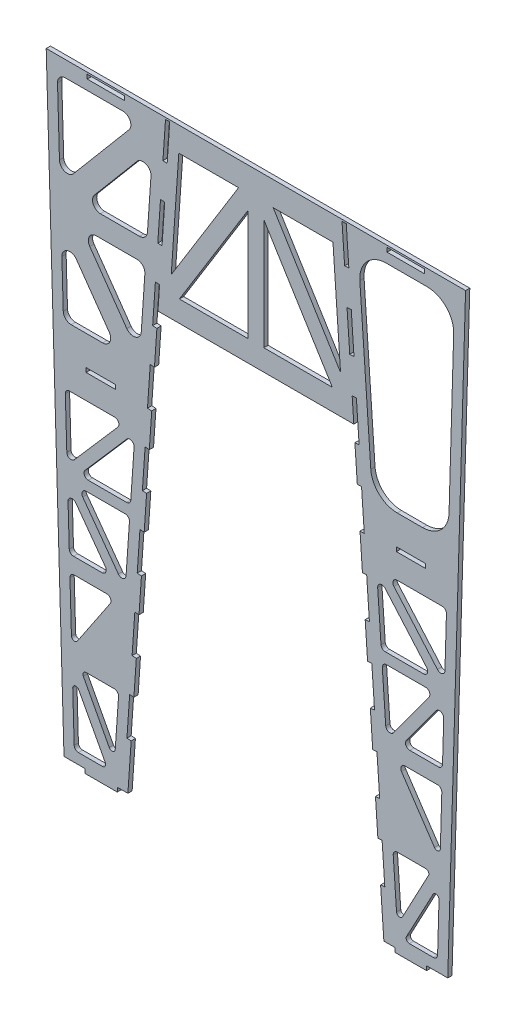
SolidWorks part; units mm, degrees
ref_plane "Front Plane" through (0, 0, 0) normal (0, 0, 1) x (1, 0, 0)
ref_plane "Top Plane" through (0, 0, 0) normal (0, 1, 0) x (1, 0, 0)
ref_plane "Right Plane" through (0, 0, 0) normal (1, 0, 0) x (0, 0, -1)
sketch "Sketch1" plane through (0, 0, 0) normal (0, 0, 1) x (1, 0, 0)
  line L0 (-288.2759, 0) -> (288.2759, 0) construction
  line L1 (-215.8925, 1465.1633) -> (215.8925, 1465.1633)
  line L2 (0, 0) -> (0, 1733.4513) construction
  line L3 (19.05, 1104.9) -> (205.6376, 1104.9)
  line L4 (202.8026, 1145.716) -> (41.4459, 1406.7433)
  line L5 (205.6376, 1104.9) -> (19.05, 1406.7433) construction
  line L6 (205.6376, 1104.9) -> (184.6725, 1406.7433)
  line L7 (183.2417, 1104.9) -> (15.2162, 1376.7154)
  line L8 (19.05, 1406.7433) -> (19.05, 1104.9)
  line L9 (184.6725, 1406.7433) -> (19.05, 1406.7433)
  line L10 (306.6278, 17.4764) -> (234.6272, 1054.1)
  line L11 (408.9218, 17.4764) -> (459.7218, 17.4764)
  line L12 (459.7218, 17.4764) -> (502.3797, 1465.1633)
  line L13 (459.4357, 7.4824) -> (519.9157, 2060.3987) construction
  line L14 (-408.9218, 17.4764) -> (-408.9218, 7.3164) construction
  line L15 (266.6925, 1465.1633) -> (368.5375, 1465.1633)
  line L16 (-237.2124, 1016.8799) -> (-230.6925, 1110.7494) construction
  line L18 (237.2124, 1016.8799) -> (230.6925, 1110.7494) construction
  line L19 (-408.9218, 7.3164) -> (-332.1008, 7.3164)
  line L20 (-502.3797, 1465.1633) -> (-215.8925, 1465.1633)
  line L21 (-408.9218, 17.4764) -> (-408.9218, 7.3164)
  line L22 (408.9218, 7.3164) -> (332.7218, 7.3164)
  line L31 (502.3797, 1465.1633) -> (368.5375, 1465.1633)
  line L33 (-332.1008, 17.4764) -> (-332.1008, 7.3164)
  line L35 (408.9218, 17.4764) -> (408.9218, 7.3164)
  line L43 (332.7218, 17.4764) -> (332.7218, 7.3164)
  line L49 (-408.9218, 17.4764) -> (-459.7218, 17.4764)
  line L52 (-332.1008, 17.4764) -> (-306.6278, 17.4764)
  line L53 (332.7218, 17.4764) -> (306.6278, 17.4764)
  line L55 (-459.7218, 17.4764) -> (-502.3797, 1465.1633)
  line L56 (-459.4357, 7.4824) -> (-519.9157, 2060.3987) construction
  line L81 (215.8925, 1465.1633) -> (266.6925, 1465.1633)
  line L90 (234.6272, 1054.1) -> (-234.6272, 1054.1)
  line L100 (-234.6272, 1054.1) -> (-306.6278, 17.4764)
  line L124 (-184.6725, 1406.7433) -> (-19.05, 1406.7433)
  line L125 (-19.05, 1406.7433) -> (-19.05, 1104.9)
  line L126 (-183.2417, 1104.9) -> (-15.2162, 1376.7154)
  line L127 (-205.6376, 1104.9) -> (-19.05, 1406.7433) construction
  line L128 (-202.8026, 1145.716) -> (-41.4459, 1406.7433)
  line L129 (-205.6376, 1104.9) -> (-184.6725, 1406.7433)
  line L130 (-19.05, 1104.9) -> (-205.6376, 1104.9)
  point P0 (0, 0)
  point P3 (0, 0)
  point P106 (0, 0)
  point P118 (0, 1054.1)
  dimension "D6" = 25.4
  dimension "D7" = 50.8
  dimension "D8" = 58.42
  dimension "D9" = 19.05
  dimension "D19" = 288.2759
  dimension "D22" = 19.05
  dimension "D23" = 19.05
  dimension "D24" = 1054.1
  dimension "D49" = 50.8
extrude "Boss-Extrude1" add sketch "Sketch1" along normal blind 10.16
fillet "Fillet1" [suppressed] radius 19.05
sketch "Sketch2" plane through (0, 0, 0) normal (0, 0, 1) x (1, 0, 0)
  line L18 (-222.6942, 1372.2749) -> (-212.5765, 1371.5721) construction
  line L56 (-216.5353, 1460.9479) -> (-222.6942, 1372.2749) construction
  line L57 (-212.5765, 1371.5721) -> (-206.3688, 1460.9479) construction
  line L58 (-206.3688, 1460.9479) -> (-216.5353, 1460.9479) construction
  line L59 (-222.6942, 1372.2749) -> (-212.5765, 1371.5721)
  line L61 (-216.5353, 1460.9479) -> (-222.6942, 1372.2749)
  line L63 (-212.5765, 1371.5721) -> (-206.3688, 1460.9479)
  line L176 (-206.3688, 1460.9479) -> (-216.5353, 1460.9479)
  line L181 (-224.8945, 1194.226) -> (-235.0121, 1194.9287) construction
  line L194 (-224.8945, 1194.226) -> (-218.3727, 1288.1221) construction
  line L199 (-218.3727, 1288.1221) -> (-228.4904, 1288.8248) construction
  line L208 (-228.4904, 1288.8248) -> (-235.0121, 1194.9287) construction
  line L213 (-224.8945, 1194.226) -> (-235.0121, 1194.9287)
  line L330 (-224.8945, 1194.226) -> (-218.3727, 1288.1221)
  line L331 (-218.3727, 1288.1221) -> (-228.4904, 1288.8248)
  line L332 (-228.4904, 1288.8248) -> (-235.0121, 1194.9287)
  line L333 (224.8945, 1194.226) -> (235.0121, 1194.9287) construction
  line L334 (235.0121, 1194.9287) -> (228.4904, 1288.8248) construction
  line L335 (218.3727, 1288.1221) -> (224.8945, 1194.226) construction
  line L336 (228.4904, 1288.8248) -> (218.3727, 1288.1221) construction
  line L337 (212.5765, 1371.5721) -> (222.6942, 1372.2749) construction
  line L338 (206.3688, 1460.9479) -> (212.5765, 1371.5721) construction
  line L339 (216.5353, 1460.9479) -> (206.3688, 1460.9479) construction
  line L340 (222.6942, 1372.2749) -> (216.5353, 1460.9479) construction
  line L341 (224.8945, 1194.226) -> (235.0121, 1194.9287)
  line L342 (235.0121, 1194.9287) -> (228.4904, 1288.8248)
  line L343 (218.3727, 1288.1221) -> (224.8945, 1194.226)
  line L344 (228.4904, 1288.8248) -> (218.3727, 1288.1221)
  line L345 (212.5765, 1371.5721) -> (222.6942, 1372.2749)
  line L346 (206.3688, 1460.9479) -> (212.5765, 1371.5721)
  line L347 (216.5353, 1460.9479) -> (206.3688, 1460.9479)
  line L348 (222.6942, 1372.2749) -> (216.5353, 1460.9479)
  line L349 (-240.8102, 1111.4521) -> (-247.33, 1017.5826) construction
  line L350 (-247.33, 1017.5826) -> (-237.2124, 1016.8799) construction
  line L351 (-230.6925, 1110.7494) -> (-240.8102, 1111.4521) construction
  line L353 (-240.8102, 1111.4521) -> (-247.33, 1017.5826)
  line L354 (-247.33, 1017.5826) -> (-237.2124, 1016.8799)
  line L355 (-230.6925, 1110.7494) -> (-240.8102, 1111.4521)
  line L357 (237.2124, 1016.8799) -> (247.33, 1017.5826) construction
  line L358 (247.33, 1017.5826) -> (240.8102, 1111.4521) construction
  line L360 (240.8102, 1111.4521) -> (230.6925, 1110.7494) construction
  line L361 (237.2124, 1016.8799) -> (247.33, 1017.5826)
  line L362 (247.33, 1017.5826) -> (240.8102, 1111.4521)
  line L364 (240.8102, 1111.4521) -> (230.6925, 1110.7494)
  line L365 (-306.6278, 17.4764) -> (-234.6272, 1054.1)
  line L366 (-234.6272, 1054.1) -> (234.6272, 1054.1)
  line L367 (234.6272, 1054.1) -> (306.6278, 17.4764)
  line L373 (459.7218, 17.4764) -> (502.3797, 1465.1633)
  line L374 (502.3797, 1465.1633) -> (-502.3797, 1465.1633)
  line L375 (-502.3797, 1465.1633) -> (-459.7218, 17.4764)
  line L376 (-459.7218, 17.4764) -> (-408.9218, 17.4764)
  line L378 (-408.9218, 7.3164) -> (-332.1008, 7.3164)
  line L379 (-332.1008, 7.3164) -> (-332.1008, 17.4764)
  line L380 (-332.1008, 17.4764) -> (-306.6278, 17.4764)
  line L381 (-298.8019, 130.1492) -> (-292.2913, 223.886)
  line L405 (-243.0122, 933.3767) -> (-253.1299, 934.0795) construction
  line L406 (-253.1299, 934.0795) -> (-259.648, 840.2365) construction
  line L407 (-249.5303, 839.5337) -> (-259.648, 840.2365) construction
  line L408 (-243.0122, 933.3767) -> (-253.1299, 934.0795)
  line L417 (-253.1299, 934.0795) -> (-259.648, 840.2365)
  line L418 (-249.5303, 839.5337) -> (-259.648, 840.2365)
  line L419 (243.0122, 933.3767) -> (253.1299, 934.0795) construction
  line L420 (253.1299, 934.0795) -> (259.648, 840.2365) construction
  line L421 (249.5303, 839.5337) -> (259.648, 840.2365) construction
  line L422 (243.0122, 933.3767) -> (253.1299, 934.0795)
  line L423 (253.1299, 934.0795) -> (259.648, 840.2365)
  line L424 (249.5303, 839.5337) -> (259.648, 840.2365)
  line L425 (-267.6517, 578.6314) -> (-277.7694, 579.3341) construction
  line L426 (-255.332, 756.0041) -> (-265.4497, 756.7068) construction
  line L427 (-265.4497, 756.7068) -> (-271.9659, 662.8903) construction
  line L428 (-261.8482, 662.1876) -> (-271.9659, 662.8903) construction
  line L429 (-277.7694, 579.3341) -> (-284.2838, 485.5442) construction
  line L430 (-274.1661, 484.8415) -> (-284.2838, 485.5442) construction
  line L431 (-274.1661, 484.8415) -> (-284.2838, 485.5442)
  line L432 (-277.7694, 579.3341) -> (-284.2838, 485.5442)
  line L433 (-267.6517, 578.6314) -> (-277.7694, 579.3341)
  line L434 (-261.8482, 662.1876) -> (-271.9659, 662.8903)
  line L435 (-265.4497, 756.7068) -> (-271.9659, 662.8903)
  line L436 (-255.332, 756.0041) -> (-265.4497, 756.7068)
  line L437 (261.8482, 662.1876) -> (271.9659, 662.8903) construction
  line L438 (255.332, 756.0041) -> (265.4497, 756.7068) construction
  line L439 (265.4497, 756.7068) -> (271.9659, 662.8903) construction
  line L440 (261.8482, 662.1876) -> (271.9659, 662.8903)
  line L449 (255.332, 756.0041) -> (265.4497, 756.7068)
  line L450 (265.4497, 756.7068) -> (271.9659, 662.8903)
  line L451 (274.1661, 484.8415) -> (284.2838, 485.5442) construction
  line L452 (277.7694, 579.3341) -> (284.2838, 485.5442) construction
  line L453 (267.6517, 578.6314) -> (277.7694, 579.3341) construction
  line L454 (274.1661, 484.8415) -> (284.2838, 485.5442)
  line L455 (277.7694, 579.3341) -> (284.2838, 485.5442)
  line L456 (267.6517, 578.6314) -> (277.7694, 579.3341)
  line L457 (-298.8019, 130.1492) -> (-308.9196, 130.8519) construction
  line L458 (-302.4089, 224.5888) -> (-308.9196, 130.8519) construction
  line L459 (-292.2913, 223.886) -> (-302.4089, 224.5888) construction
  line L460 (-286.484, 307.4953) -> (-296.6017, 308.1981) construction
  line L461 (-290.0892, 401.9615) -> (-296.6017, 308.1981) construction
  line L462 (-279.9715, 401.2587) -> (-290.0892, 401.9615) construction
  line L463 (-298.8019, 130.1492) -> (-308.9196, 130.8519)
  line L464 (-302.4089, 224.5888) -> (-308.9196, 130.8519)
  line L465 (-292.2913, 223.886) -> (-302.4089, 224.5888)
  line L466 (-286.484, 307.4953) -> (-296.6017, 308.1981)
  line L467 (-290.0892, 401.9615) -> (-296.6017, 308.1981)
  line L468 (-279.9715, 401.2587) -> (-290.0892, 401.9615)
  line L469 (286.484, 307.4953) -> (296.6017, 308.1981) construction
  line L470 (279.9715, 401.2587) -> (290.0892, 401.9615) construction
  line L471 (290.0892, 401.9615) -> (296.6017, 308.1981) construction
  line L472 (286.484, 307.4953) -> (296.6017, 308.1981)
  line L473 (279.9715, 401.2587) -> (290.0892, 401.9615)
  line L474 (290.0892, 401.9615) -> (296.6017, 308.1981)
  line L475 (298.8019, 130.1492) -> (308.9196, 130.8519) construction
  line L476 (302.4089, 224.5888) -> (308.9196, 130.8519) construction
  line L477 (292.2913, 223.886) -> (302.4089, 224.5888) construction
  line L478 (298.8019, 130.1492) -> (308.9196, 130.8519)
  line L479 (302.4089, 224.5888) -> (308.9196, 130.8519)
  line L480 (292.2913, 223.886) -> (302.4089, 224.5888)
  line L481 (-230.6925, 1110.7494) -> (-237.2124, 1016.8799)
  line L482 (243.0122, 933.3767) -> (249.5303, 839.5337)
  line L483 (255.332, 756.0041) -> (261.8482, 662.1876)
  line L484 (-249.5303, 839.5337) -> (-243.0122, 933.3767)
  line L485 (-261.8482, 662.1876) -> (-255.332, 756.0041)
  line L486 (267.6517, 578.6314) -> (274.1661, 484.8415)
  line L487 (-286.484, 307.4953) -> (-279.9715, 401.2587)
  line L488 (-274.1661, 484.8415) -> (-267.6517, 578.6314)
  line L489 (279.9715, 401.2587) -> (286.484, 307.4953)
  line L490 (292.2913, 223.886) -> (298.8019, 130.1492)
  line L492 (230.6925, 1110.7494) -> (237.2124, 1016.8799)
  line L499 (306.6278, 17.4764) -> (332.7218, 17.4764)
  line L500 (332.7218, 17.4764) -> (332.7218, 7.3164)
  line L501 (332.7218, 7.3164) -> (408.9218, 7.3164)
  line L502 (408.9218, 7.3164) -> (408.9218, 17.4764)
  line L503 (408.9218, 17.4764) -> (459.7218, 17.4764)
  line L505 (-408.9218, 17.4764) -> (-408.9218, 7.3164)
  dimension "D1" = 0
extrude "Cut-Extrude5" cut sketch "Sketch2" along normal blind 12.7
sketch "Sketch4" plane through (0, 0, 10.16) normal (0, 0, 1) x (1, 0, 0)
  line L0 (404.198, 1450.7879) -> (404.198, 1460.9479) construction
  line L1 (314.198, 1450.7879) -> (404.198, 1450.7879) construction
  line L2 (314.198, 1450.7879) -> (314.198, 1460.9479) construction
  line L3 (404.198, 1460.9479) -> (314.198, 1460.9479) construction
  line L4 (404.198, 1450.7879) -> (404.198, 1460.9479)
  line L5 (314.198, 1450.7879) -> (404.198, 1450.7879)
  line L6 (314.198, 1450.7879) -> (314.198, 1460.9479)
  line L7 (404.198, 1460.9479) -> (314.198, 1460.9479)
  line L8 (336.7731, 840.6279) -> (336.7731, 850.7879) construction
  line L9 (336.7731, 840.6279) -> (406.7731, 840.6279) construction
  line L10 (406.7731, 840.6279) -> (406.7731, 850.7879) construction
  line L11 (406.7731, 850.7879) -> (336.7731, 850.7879) construction
  line L12 (336.7731, 840.6279) -> (336.7731, 850.7879)
  line L13 (336.7731, 840.6279) -> (406.7731, 840.6279)
  line L14 (406.7731, 840.6279) -> (406.7731, 850.7879)
  line L15 (406.7731, 850.7879) -> (336.7731, 850.7879)
extrude "Cut-Extrude6" cut sketch "Sketch4" against normal through all both
ref_plane "Plane1" through (0, 0, 0) normal (1, 0, 0) x (0, 0, -1)
mirror "Mirror1" about plane through (0, 0, 0) normal (1, 0, 0) of "Cut-Extrude6"
sketch "Sketch5" plane through (0, 0, 10.16) normal (0, 0, 1) x (1, 0, 0)
  line L0 (435.0592, 42.8763) -> (475.846, 1427.0633)
  line L1 (475.846, 1427.0633) -> (244.3499, 1427.0633)
  line L2 (244.3499, 1427.0633) -> (340.4914, 42.8763)
  line L3 (340.4914, 42.8763) -> (435.0592, 42.8763)
  line L4 (281.2006, 896.5079) -> (460.2126, 896.5079)
  line L5 (457.2188, 794.9079) -> (288.2575, 794.9079)
  line L6 (336.7731, 840.6279) -> (406.7731, 840.6279) construction
  line L7 (475.846, 1427.0633) -> (460.2126, 896.5079)
  line L8 (468.0293, 1161.7856) -> (281.2006, 896.5079) construction
  line L9 (244.3499, 1427.0633) -> (468.0293, 1161.7856) construction
  line L10 (244.3499, 1427.0633) -> (281.2006, 896.5079)
  line L11 (281.2006, 896.5079) -> (244.3499, 1427.0633)
  line L12 (262.7753, 1161.7856) -> (468.0293, 1161.7856) construction
  line L13 (435.0592, 42.8763) -> (457.2188, 794.9079)
  line L14 (446.139, 418.8921) -> (457.2188, 794.9079)
  line L15 (451.6789, 606.9) -> (288.2575, 794.9079) construction
  line L16 (451.6789, 606.9) -> (314.3744, 418.8921) construction
  line L17 (446.139, 418.8921) -> (435.0592, 42.8763)
  line L18 (440.5991, 230.8842) -> (314.3744, 418.8921) construction
  line L19 (440.5991, 230.8842) -> (340.4914, 42.8763) construction
  line L20 (451.6789, 606.9) -> (301.3159, 606.9) construction
  line L21 (314.3744, 418.8921) -> (446.139, 418.8921) construction
  line L22 (440.5991, 230.8842) -> (327.4329, 230.8842) construction
  line L23 (354.8795, 42.8763) -> (439.7562, 202.2795)
  line L24 (338.8311, 66.78) -> (419.4486, 218.1842)
  line L25 (328.315, 218.1842) -> (419.4486, 218.1842)
  line L26 (326.5508, 243.5842) -> (416.7758, 243.5842)
  line L27 (416.7758, 243.5842) -> (316.1395, 393.4789)
  line L28 (441.2422, 252.7104) -> (338.1977, 406.1921)
  line L29 (338.1977, 406.1921) -> (445.7648, 406.1921)
  line L30 (446.8874, 444.2921) -> (348.6506, 444.2921)
  line L31 (348.6506, 444.2921) -> (451.0177, 584.4611)
  line L32 (313.0087, 438.5556) -> (426.6777, 594.2)
  line L33 (426.6777, 594.2) -> (302.1981, 594.2)
  line L34 (300.4338, 619.6) -> (423.8126, 619.6)
  line L35 (423.8126, 619.6) -> (289.7189, 773.8679)
  line L36 (452.2306, 625.6241) -> (316.1238, 782.2079)
  line L37 (316.1238, 782.2079) -> (456.8446, 782.2079)
  line L38 (277.5741, 1427.0633) -> (469.1512, 1199.8581)
  line L39 (247.3324, 1384.1231) -> (413.3881, 1187.1856)
  line L40 (413.3881, 1187.1856) -> (261.011, 1187.1856)
  line L41 (264.5395, 1136.3856) -> (419.0736, 1136.3856)
  line L42 (419.0736, 1136.3856) -> (278.4118, 936.6601)
  line L43 (466.6727, 1115.7473) -> (330.1563, 921.9079)
  line L44 (330.1563, 921.9079) -> (460.961, 921.9079)
  line L61 (408.9218, 17.4764) -> (459.7218, 17.4764)
  line L62 (408.9218, 17.4764) -> (459.7218, 17.4764)
  line L63 (-408.9218, 17.4764) -> (-408.9218, 7.3164)
  line L64 (-234.6272, 1054.1) -> (234.6272, 1054.1)
  line L65 (-408.9218, 17.4764) -> (-408.9218, 7.3164)
  line L69 (237.2124, 1016.8799) -> (243.0122, 933.3767)
  line L90 (306.6278, 17.4764) -> (332.7218, 17.4764)
  line L91 (332.7218, 17.4764) -> (332.7218, 7.3164)
  line L92 (332.7218, 7.3164) -> (408.9218, 7.3164)
  line L93 (408.9218, 7.3164) -> (408.9218, 17.4764)
  line L95 (459.7218, 17.4764) -> (502.3797, 1465.1633)
  line L96 (502.3797, 1465.1633) -> (-502.3797, 1465.1633)
  line L97 (-502.3797, 1465.1633) -> (-459.7218, 17.4764)
  line L98 (-459.7218, 17.4764) -> (-408.9218, 17.4764)
  line L100 (-408.9218, 7.3164) -> (-332.1008, 7.3164)
  line L101 (-332.1008, 7.3164) -> (-332.1008, 17.4764)
  line L102 (-332.1008, 17.4764) -> (-306.6278, 17.4764)
  line L103 (-306.6278, 17.4764) -> (-298.8019, 130.1492)
  line L127 (234.6272, 1054.1) -> (230.6925, 1110.7494)
  line L128 (-234.6272, 1054.1) -> (234.6272, 1054.1)
  line L133 (237.2124, 1016.8799) -> (243.0122, 933.3767)
  line L154 (306.6278, 17.4764) -> (332.7218, 17.4764)
  line L155 (332.7218, 17.4764) -> (332.7218, 7.3164)
  line L156 (332.7218, 7.3164) -> (408.9218, 7.3164)
  line L157 (408.9218, 7.3164) -> (408.9218, 17.4764)
  line L159 (459.7218, 17.4764) -> (502.3797, 1465.1633)
  line L160 (502.3797, 1465.1633) -> (-502.3797, 1465.1633)
  line L161 (-502.3797, 1465.1633) -> (-459.7218, 17.4764)
  line L162 (-459.7218, 17.4764) -> (-408.9218, 17.4764)
  line L164 (-408.9218, 7.3164) -> (-332.1008, 7.3164)
  line L165 (-332.1008, 7.3164) -> (-332.1008, 17.4764)
  line L166 (-332.1008, 17.4764) -> (-306.6278, 17.4764)
  line L167 (-306.6278, 17.4764) -> (-298.8019, 130.1492)
  line L192 (234.6272, 1054.1) -> (230.6925, 1110.7494)
  line L193 (230.6925, 1110.7494) -> (240.8102, 1111.4521)
  line L194 (230.6925, 1110.7494) -> (240.8102, 1111.4521)
  line L195 (240.8102, 1111.4521) -> (247.33, 1017.5826)
  line L196 (240.8102, 1111.4521) -> (247.33, 1017.5826)
  line L197 (247.33, 1017.5826) -> (237.2124, 1016.8799)
  line L198 (247.33, 1017.5826) -> (237.2124, 1016.8799)
  line L199 (243.0122, 933.3767) -> (253.1299, 934.0795)
  line L200 (243.0122, 933.3767) -> (253.1299, 934.0795)
  line L201 (253.1299, 934.0795) -> (259.648, 840.2365)
  line L202 (253.1299, 934.0795) -> (259.648, 840.2365)
  line L203 (259.648, 840.2365) -> (249.5303, 839.5337)
  line L204 (259.648, 840.2365) -> (249.5303, 839.5337)
  line L205 (249.5303, 839.5337) -> (255.332, 756.0041)
  line L206 (249.5303, 839.5337) -> (255.332, 756.0041)
  line L207 (255.332, 756.0041) -> (265.4497, 756.7068)
  line L208 (255.332, 756.0041) -> (265.4497, 756.7068)
  line L209 (265.4497, 756.7068) -> (271.9659, 662.8903)
  line L210 (265.4497, 756.7068) -> (271.9659, 662.8903)
  line L211 (271.9659, 662.8903) -> (261.8482, 662.1876)
  line L212 (271.9659, 662.8903) -> (261.8482, 662.1876)
  line L213 (261.8482, 662.1876) -> (267.6517, 578.6314)
  line L214 (261.8482, 662.1876) -> (267.6517, 578.6314)
  line L215 (267.6517, 578.6314) -> (277.7694, 579.3341)
  line L216 (267.6517, 578.6314) -> (277.7694, 579.3341)
  line L217 (277.7694, 579.3341) -> (284.2838, 485.5442)
  line L218 (277.7694, 579.3341) -> (284.2838, 485.5442)
  line L219 (284.2838, 485.5442) -> (274.1661, 484.8415)
  line L220 (284.2838, 485.5442) -> (274.1661, 484.8415)
  line L221 (274.1661, 484.8415) -> (279.9715, 401.2587)
  line L222 (274.1661, 484.8415) -> (279.9715, 401.2587)
  line L223 (279.9715, 401.2587) -> (290.0892, 401.9615)
  line L224 (279.9715, 401.2587) -> (290.0892, 401.9615)
  line L225 (290.0892, 401.9615) -> (296.6017, 308.1981)
  line L226 (290.0892, 401.9615) -> (296.6017, 308.1981)
  line L227 (296.6017, 308.1981) -> (286.484, 307.4953)
  line L228 (296.6017, 308.1981) -> (286.484, 307.4953)
  line L229 (286.484, 307.4953) -> (292.2913, 223.886)
  line L230 (286.484, 307.4953) -> (292.2913, 223.886)
  line L231 (292.2913, 223.886) -> (302.4089, 224.5888)
  line L232 (292.2913, 223.886) -> (302.4089, 224.5888)
  line L233 (302.4089, 224.5888) -> (308.9196, 130.8519)
  line L234 (302.4089, 224.5888) -> (308.9196, 130.8519)
  line L235 (308.9196, 130.8519) -> (298.8019, 130.1492)
  line L236 (308.9196, 130.8519) -> (298.8019, 130.1492)
  line L237 (298.8019, 130.1492) -> (306.6278, 17.4764)
  line L238 (298.8019, 130.1492) -> (306.6278, 17.4764)
  line L239 (-298.8019, 130.1492) -> (-308.9196, 130.8519)
  line L240 (-298.8019, 130.1492) -> (-308.9196, 130.8519)
  line L241 (-308.9196, 130.8519) -> (-302.4089, 224.5888)
  line L242 (-308.9196, 130.8519) -> (-302.4089, 224.5888)
  line L243 (-302.4089, 224.5888) -> (-292.2913, 223.886)
  line L244 (-302.4089, 224.5888) -> (-292.2913, 223.886)
  line L245 (-292.2913, 223.886) -> (-286.484, 307.4953)
  line L246 (-292.2913, 223.886) -> (-286.484, 307.4953)
  line L247 (-286.484, 307.4953) -> (-296.6017, 308.1981)
  line L248 (-286.484, 307.4953) -> (-296.6017, 308.1981)
  line L249 (-296.6017, 308.1981) -> (-290.0892, 401.9615)
  line L250 (-296.6017, 308.1981) -> (-290.0892, 401.9615)
  line L251 (-290.0892, 401.9615) -> (-279.9715, 401.2587)
  line L252 (-290.0892, 401.9615) -> (-279.9715, 401.2587)
  line L253 (-279.9715, 401.2587) -> (-274.1661, 484.8415)
  line L254 (-279.9715, 401.2587) -> (-274.1661, 484.8415)
  line L255 (-274.1661, 484.8415) -> (-284.2838, 485.5442)
  line L256 (-274.1661, 484.8415) -> (-284.2838, 485.5442)
  line L257 (-284.2838, 485.5442) -> (-277.7694, 579.3341)
  line L258 (-284.2838, 485.5442) -> (-277.7694, 579.3341)
  line L259 (-277.7694, 579.3341) -> (-267.6517, 578.6314)
  line L260 (-277.7694, 579.3341) -> (-267.6517, 578.6314)
  line L261 (-267.6517, 578.6314) -> (-261.8482, 662.1876)
  line L262 (-267.6517, 578.6314) -> (-261.8482, 662.1876)
  line L263 (-261.8482, 662.1876) -> (-271.9659, 662.8903)
  line L264 (-261.8482, 662.1876) -> (-271.9659, 662.8903)
  line L265 (-271.9659, 662.8903) -> (-265.4497, 756.7068)
  line L266 (-271.9659, 662.8903) -> (-265.4497, 756.7068)
  line L267 (-265.4497, 756.7068) -> (-255.332, 756.0041)
  line L268 (-265.4497, 756.7068) -> (-255.332, 756.0041)
  line L269 (-255.332, 756.0041) -> (-249.5303, 839.5337)
  line L270 (-255.332, 756.0041) -> (-249.5303, 839.5337)
  line L271 (-249.5303, 839.5337) -> (-259.648, 840.2365)
  line L272 (-249.5303, 839.5337) -> (-259.648, 840.2365)
  line L273 (-259.648, 840.2365) -> (-253.1299, 934.0795)
  line L274 (-259.648, 840.2365) -> (-253.1299, 934.0795)
  line L275 (-253.1299, 934.0795) -> (-243.0122, 933.3767)
  line L276 (-253.1299, 934.0795) -> (-243.0122, 933.3767)
  line L277 (-243.0122, 933.3767) -> (-237.2124, 1016.8799)
  line L278 (-243.0122, 933.3767) -> (-237.2124, 1016.8799)
  line L279 (-237.2124, 1016.8799) -> (-247.33, 1017.5826)
  line L280 (-237.2124, 1016.8799) -> (-247.33, 1017.5826)
  line L281 (-247.33, 1017.5826) -> (-240.8102, 1111.4521)
  line L282 (-247.33, 1017.5826) -> (-240.8102, 1111.4521)
  line L283 (-240.8102, 1111.4521) -> (-230.6925, 1110.7494)
  line L284 (-240.8102, 1111.4521) -> (-230.6925, 1110.7494)
  line L285 (-230.6925, 1110.7494) -> (-234.6272, 1054.1)
  line L286 (-230.6925, 1110.7494) -> (-234.6272, 1054.1)
  dimension "D2" = 38.1
  dimension "D3" = 25.4
  dimension "D6" = 101.6
  dimension "D7" = 45.72
  dimension "D8" = 12.7
  dimension "D9" = 12.7
  dimension "D10" = 12.7
  dimension "D11" = 12.7
  dimension "D12" = 12.7
  dimension "D13" = 12.7
  dimension "D14" = 12.7
  dimension "D15" = 25.4
  dimension "D16" = 12.7
  dimension "D17" = 12.7
  dimension "D18" = 12.7
  dimension "D19" = 12.7
  dimension "D20" = 12.7
  dimension "D21" = 12.7
  dimension "D22" = 12.7
  dimension "D23" = 25.4
  dimension "D24" = 25.4
  dimension "D25" = 25.4
  dimension "D26" = 25.4
  dimension "D27" = 25.4
  dimension "D28" = 25.4
  dimension "D29" = 25.4
  dimension "D1" = 0
extrude "Cut-Extrude7" cut sketch "Sketch5" against normal through all both contours L1 L38 L7 | L40 L39 L11 | L42 L41 L11 | L43 L44 L7 | L37 L36 L14 | L34 L35 L2 | L32 L33 L2 | L31 L30 L14 | L29 L28 L0 | L26 L27 L2 | L25 L2 L24 | L23 L3 L0
fillet "Fillet3" radius 10.16 18 edges at (423.8126, 619.6, 5.08) (300.4338, 619.6, 5.08) (289.7189, 773.8679, 5.08) (426.6777, 594.2, 5.08) (313.0087, 438.5556, 5.08) (302.1981, 594.2, 5.08) (348.6506, 444.2921, 5.08) (451.0177, 584.4611, 5.08) (446.8874, 444.2921, 5.08) (338.1977, 406.1921, 5.08) (445.7648, 406.1921, 5.08) (316.1238, 782.2079, 5.08) (456.8446, 782.2079, 5.08) (452.2306, 625.6241, 5.08) (435.0592, 42.8763, 5.08) (328.315, 218.1842, 5.08) (416.7758, 243.5842, 5.08) (326.5508, 243.5842, 5.08)
fillet "Fillet4" radius 7.62 6 edges at (441.2422, 252.7104, 5.08) (354.8795, 42.8763, 5.08) (439.7562, 202.2795, 5.08) (419.4486, 218.1842, 5.08) (338.8311, 66.78, 5.08) (316.1395, 393.4789, 5.08)
fillet "Fillet5" radius 19.05 12 edges at (330.1563, 921.9079, 5.08) (460.961, 921.9079, 5.08) (419.0736, 1136.3856, 5.08) (466.6727, 1115.7473, 5.08) (475.846, 1427.0633, 5.08) (469.1512, 1199.8581, 5.08) (413.3881, 1187.1856, 5.08) (277.5741, 1427.0633, 5.08) (247.3324, 1384.1231, 5.08) (264.5395, 1136.3856, 5.08) (261.011, 1187.1856, 5.08) (278.4118, 936.6601, 5.08)
mirror "Mirror2" about plane through (0, 0, 0) normal (1, 0, 0) of "Cut-Extrude7", "Fillet3", "Fillet4", "Fillet5"
sketch "Sketch6" plane through (0, 0, 10.16) normal (0, 0, 1) x (1, 0, 0)
  line L0 (244.3499, 1427.0633) -> (279.4364, 921.9079)
  line L1 (279.4364, 921.9079) -> (460.961, 921.9079)
  line L2 (460.961, 921.9079) -> (475.846, 1427.0633)
  line L3 (366.8731, 921.9079) -> (442.4641, 921.9079) construction
  line L4 (244.3499, 1427.0633) -> (475.846, 1427.0633)
  line L5 (470.6195, 1249.6908) -> (475.2682, 1407.4522) construction
  line L6 (251.3751, 1325.9178) -> (259.7796, 1204.9156) construction
  line L7 (456.2264, 1427.0633) -> (318.555, 1427.0633) construction
extrude "Cut-Extrude8" cut sketch "Sketch6" against normal through all both
fillet "Fillet6" radius 63.5 4 edges at (475.846, 1427.0633, 5.08) (460.961, 921.9079, 5.08) (279.4364, 921.9079, 5.08) (244.3499, 1427.0633, 5.08)
sketch "Sketch7" plane through (0, 0, 10.16) normal (0, 0, 1) x (1, 0, 0)
  line L0 (-336.0296, 243.5842) -> (-397.7172, 243.5842) construction
  line L1 (-318.1167, 365.0131) -> (-325.894, 253.0402) construction
  line L2 (-406.1524, 259.4075) -> (-332.0448, 369.7885) construction
  line L3 (-336.0296, 243.5842) -> (-397.7172, 243.5842)
  line L4 (-318.1167, 365.0131) -> (-325.894, 253.0402)
  line L5 (-406.1524, 259.4075) -> (-332.0448, 369.7885)
  arc A0 (-406.1524, 259.4075) -> (-397.7172, 243.5842) centre (-397.7172, 253.7442) ccw construction
  arc A1 (-336.0296, 243.5842) -> (-325.894, 253.0402) centre (-336.0296, 253.7442) ccw construction
  arc A2 (-318.1167, 365.0131) -> (-332.0448, 369.7885) centre (-325.7184, 365.5411) ccw construction
  arc A3 (-406.1524, 259.4075) -> (-397.7172, 243.5842) centre (-397.7172, 253.7442) ccw
  arc A4 (-336.0296, 243.5842) -> (-325.894, 253.0402) centre (-336.0296, 253.7442) ccw
  arc A5 (-318.1167, 365.0131) -> (-332.0448, 369.7885) centre (-325.7184, 365.5411) ccw
extrude "Boss-Extrude2" add sketch "Sketch7" against normal up to surface (10.16 mm away) contours A3 L3 A4 L4 A5 L5 up to face at (-346.4743, 545.9059, 0)
mirror "Mirror3" about plane through (0, 0, 0) normal (1, 0, 0) of "Boss-Extrude2"
